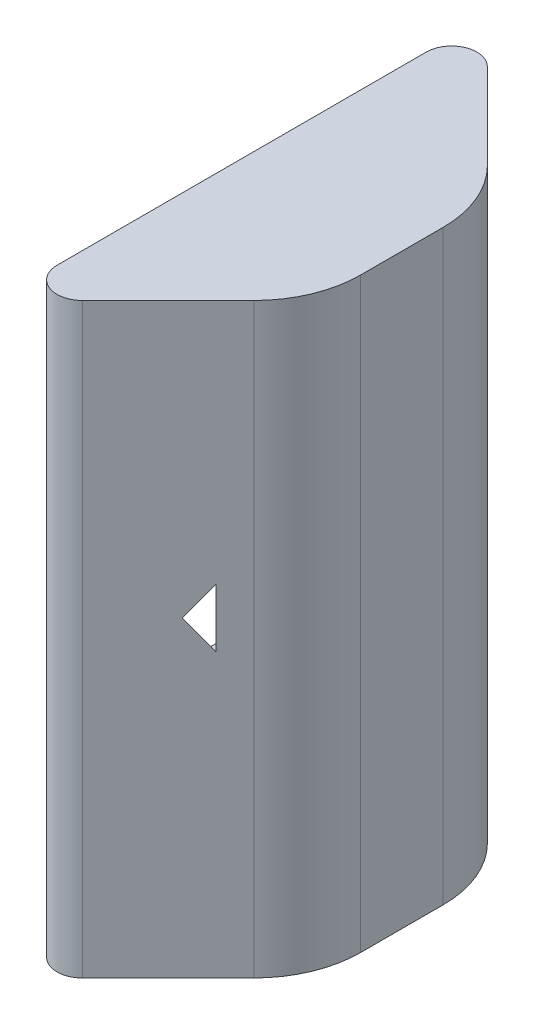
SolidWorks part; units mm, degrees
ref_plane "Front Plane" through (0, 0, 0) normal (0, 0, 1) x (1, 0, 0)
ref_plane "Top Plane" through (0, 0, 0) normal (0, 1, 0) x (1, 0, 0)
ref_plane "Right Plane" through (0, 0, 0) normal (1, 0, 0) x (0, 0, -1)
sketch "Sketch1" plane through (0, 887.3681, 0) normal (0, 1, 0) x (1, 0, 0)
  line L0 (637.8137, -1272.1875) -> (637.8137, -1269.9384) construction
  line L1 (636.9614, -1267.8807) -> (634.6216, -1265.5409) construction
  line L2 (633.4437, -1266.0288) -> (633.4437, -1268.1979) construction
  line L3 (633.4437, -1273.9279) -> (633.4437, -1276.097) construction
  line L4 (634.6216, -1276.585) -> (636.9614, -1274.2452) construction
  line L5 (637.8137, -1272.1875) -> (637.8137, -1269.9384)
  line L6 (636.9614, -1267.8807) -> (634.6216, -1265.5409)
  line L7 (633.4437, -1266.0288) -> (633.4437, -1268.1979)
  line L8 (633.4437, -1273.9279) -> (633.4437, -1276.097)
  line L9 (634.6216, -1276.585) -> (636.9614, -1274.2452)
  line L10 (633.4437, -1268.1979) -> (633.4437, -1273.9279)
  arc A0 (637.8137, -1269.9384) -> (636.9614, -1267.8807) centre (634.9037, -1269.9384) ccw construction
  arc A1 (634.6216, -1265.5409) -> (633.4437, -1266.0288) centre (634.1337, -1266.0288) ccw construction
  arc A2 (633.4437, -1276.097) -> (634.6216, -1276.585) centre (634.1337, -1276.097) ccw construction
  arc A3 (636.9614, -1274.2452) -> (637.8137, -1272.1875) centre (634.9037, -1272.1875) ccw construction
  arc A4 (637.8137, -1269.9384) -> (636.9614, -1267.8807) centre (634.9037, -1269.9384) ccw
  arc A5 (634.6216, -1265.5409) -> (633.4437, -1266.0288) centre (634.1337, -1266.0288) ccw
  arc A6 (633.4437, -1276.097) -> (634.6216, -1276.585) centre (634.1337, -1276.097) ccw
  arc A7 (636.9614, -1274.2452) -> (637.8137, -1272.1875) centre (634.9037, -1272.1875) ccw
extrude "Boss-Extrude1" add sketch "Sketch1" along normal mid plane 16 from offset 3
sketch "Sketch2" plane through (633.4432, 0, -0.0002) normal (-1, 0, 0) x (0, 0, 1)
  line L0 (1269.0451, 887.3681) -> (1268.0347, 889.1181) construction
  line L1 (1269.0451, 887.3681) -> (1271.0658, 887.3681) construction
  line L2 (1271.0658, 887.3681) -> (1273.0866, 887.3681) construction
  line L3 (1274.0969, 889.1181) -> (1273.0866, 887.3681) construction
  line L4 (1275.1073, 890.8681) -> (1274.0969, 889.1181) construction
  line L5 (1274.0969, 892.6181) -> (1275.1073, 890.8681) construction
  line L6 (1273.0866, 894.3681) -> (1274.0969, 892.6181) construction
  line L7 (1273.0866, 894.3681) -> (1271.0658, 894.3681) construction
  line L8 (1271.0658, 894.3681) -> (1269.0451, 894.3681) construction
  line L9 (1268.0347, 892.6181) -> (1269.0451, 894.3681) construction
  line L10 (1268.0347, 889.1181) -> (1267.0244, 890.8681) construction
  line L11 (1267.0244, 890.8681) -> (1268.0347, 892.6181) construction
  line L12 (1269.0451, 887.3681) -> (1268.0347, 889.1181) construction
  line L13 (1269.0451, 887.3681) -> (1271.0658, 887.3681) construction
  line L14 (1271.0658, 887.3681) -> (1273.0866, 887.3681) construction
  line L15 (1274.0969, 889.1181) -> (1273.0866, 887.3681) construction
  line L16 (1275.1073, 890.8681) -> (1274.0969, 889.1181) construction
  line L17 (1274.0969, 892.6181) -> (1275.1073, 890.8681) construction
  line L18 (1273.0866, 894.3681) -> (1274.0969, 892.6181) construction
  line L19 (1273.0866, 894.3681) -> (1271.0658, 894.3681) construction
  line L20 (1271.0658, 894.3681) -> (1269.0451, 894.3681) construction
  line L21 (1268.0347, 892.6181) -> (1269.0451, 894.3681) construction
  line L22 (1268.0347, 889.1181) -> (1267.0244, 890.8681) construction
  line L23 (1267.0244, 890.8681) -> (1268.0347, 892.6181) construction
  line L24 (1268.9874, 887.2681) -> (1267.9481, 889.0681)
  line L25 (1267.9481, 889.0681) -> (1266.9089, 890.8681)
  line L26 (1266.9089, 890.8681) -> (1267.9481, 892.6681)
  line L27 (1267.9481, 892.6681) -> (1268.9874, 894.4681)
  line L28 (1271.0658, 894.4681) -> (1268.9874, 894.4681)
  line L29 (1273.1443, 894.4681) -> (1271.0658, 894.4681)
  line L30 (1273.1443, 894.4681) -> (1274.1835, 892.6681)
  line L31 (1274.1835, 892.6681) -> (1275.2227, 890.8681)
  line L32 (1275.2227, 890.8681) -> (1274.1835, 889.0681)
  line L33 (1274.1835, 889.0681) -> (1273.1443, 887.2681)
  line L34 (1271.0658, 887.2681) -> (1273.1443, 887.2681)
  line L35 (1268.9874, 887.2681) -> (1271.0658, 887.2681)
  dimension "D1" = 0.1
extrude "Cut-Extrude1" cut sketch "Sketch2" against normal blind 3
